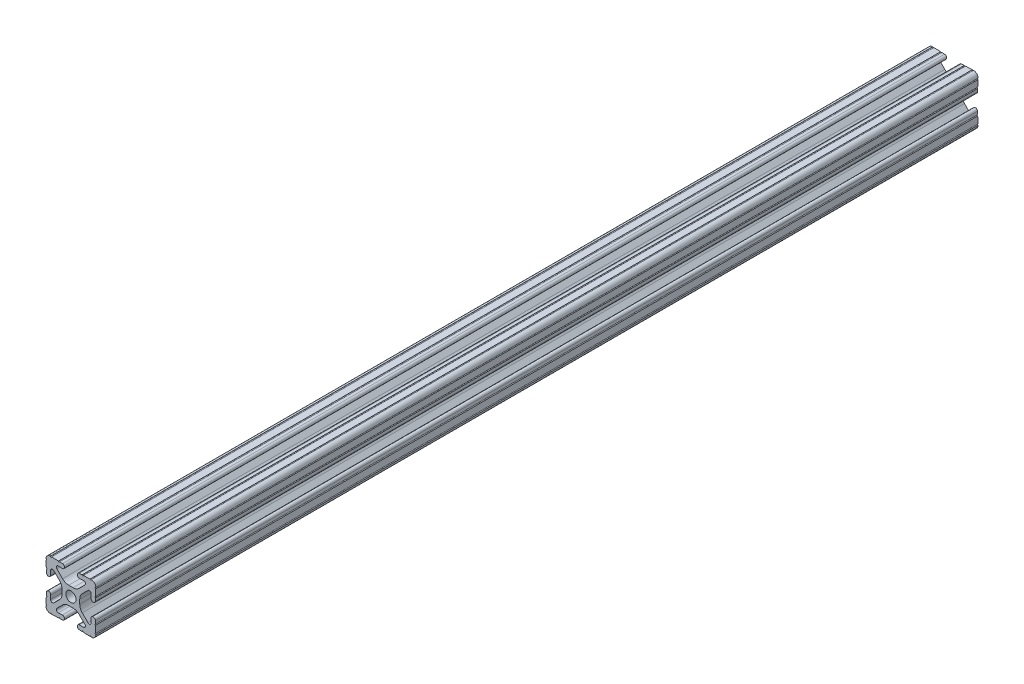
SolidWorks part; units mm, degrees
ref_plane "Front Plane" through (0, 0, 0) normal (0, 0, 1) x (1, 0, 0)
ref_plane "Top Plane" through (0, 0, 0) normal (0, 1, 0) x (1, 0, 0)
ref_plane "Right Plane" through (0, 0, 0) normal (1, 0, 0) x (0, 0, -1)
sketch "Sketch1" plane through (0, 0, 0) normal (0, 0, 1) x (1, 0, 0)
  line L0 (0, 12.7) -> (-12.7814, 12.7) construction
  line L1 (-4.5085, 0) -> (-4.5085, 2.9459)
  line L2 (-6.0437, 12.5461) -> (-10.0976, 12.6876) construction
  line L3 (-11.5616, 12.4229) -> (-4.3159, 12.1699) construction
  line L4 (-6.4364, 10.3486) -> (-6.3592, 12.5571) construction
  line L6 (-2.9459, 4.5085) -> (0, 4.5085)
  line L7 (0, 0) -> (0, 12.7) construction
  line L8 (0, 0) -> (-12.7814, 0) construction
  line L9 (0.7813, 0.7813) -> (-0.7813, -0.7813) construction
  line L10 (-2.9459, 4.5085) -> (-7.1484, 8.711)
  line L11 (-4.5085, 2.9459) -> (-8.711, 7.1484)
  line L13 (0, 0) -> (-12.7814, 12.7814) construction
  line L14 (-10.4131, 12.6987) -> (-4.3048, 12.4853)
  line L15 (-4.3048, 12.4853) -> (-4.382, 10.2769) construction
  line L16 (-4.382, 10.2769) -> (-6.4364, 10.3486)
  line L17 (-12.6987, 10.4131) -> (-12.4853, 4.3048)
  line L18 (-10.2769, 4.382) -> (-10.3486, 6.4364)
  circle A0 centre (0, 0) radius 2.6035
  arc A1 (-4.382, 10.2769) -> (-4.3048, 12.4853) centre (-4.3434, 11.3811) ccw
  arc A2 (-7.1484, 8.711) -> (-6.4364, 10.3486) centre (-6.4698, 9.3896) cw
  arc A3 (-8.711, 7.1484) -> (-10.3486, 6.4364) centre (-9.3896, 6.4698) ccw
  arc A4 (-10.2769, 4.382) -> (-12.4853, 4.3048) centre (-11.3811, 4.3434) cw
  arc A5 (-10.4131, 12.6987) -> (-12.6987, 10.4131) centre (-10.4902, 10.4902) ccw
  arc A6 (-10.4131, 12.6987) -> (-9.7821, 12.6766) centre (-10.0976, 12.6876) ccw
  arc A7 (-6.3592, 12.5571) -> (-5.7282, 12.5351) centre (-6.0437, 12.5461) ccw
  arc A8 (-12.5571, 6.3592) -> (-12.5351, 5.7282) centre (-12.5461, 6.0437) cw
  arc A9 (-12.6987, 10.4131) -> (-12.6766, 9.7821) centre (-12.6876, 10.0976) cw
  dimension "D1" = 5.207
  dimension "D5" = 14.859
  dimension "D9" = 2
  dimension "D2" = 25.4
  dimension "D12" = 0.6314
  dimension "D10" = 2.2098
  dimension "D3" = 9.017
  dimension "D4" = 9.017
  dimension "D6" = 25.4
  dimension "D7" = 6.477
  dimension "D8" = 2.2098
  dimension "D11" = 12.7
sketch "Sketch3" plane through (0, 0, 0) normal (0, 0, 1) x (1, 0, 0)
  line L0 (-2.9459, 4.5085) -> (0, 4.5085) construction
  line L1 (-2.9459, 4.5085) -> (-7.1484, 8.711) construction
  line L2 (-4.382, 10.2769) -> (-6.4364, 10.3486) construction
  line L3 (-10.4131, 12.6987) -> (-4.3048, 12.4853) construction
  line L4 (-4.5085, 0) -> (-4.5085, 2.9459) construction
  line L5 (-4.5085, 2.9459) -> (-8.711, 7.1484) construction
  line L6 (-10.2769, 4.382) -> (-10.3486, 6.4364) construction
  line L7 (-12.6987, 10.4131) -> (-12.4853, 4.3048) construction
  line L8 (-1.1153, 4.5085) -> (1.1153, 4.5085)
  line L9 (-4.2404, 5.803) -> (-7.1484, 8.711)
  line L10 (-4.382, 10.2769) -> (-6.4364, 10.3486)
  line L11 (-9.7821, 12.6766) -> (-6.3592, 12.5571)
  line L12 (-4.5085, -1.1153) -> (-4.5085, 1.1153)
  line L13 (-5.803, 4.2404) -> (-8.711, 7.1484)
  line L14 (-10.2769, 4.382) -> (-10.3486, 6.4364)
  line L15 (-12.6766, 9.7821) -> (-12.5571, 6.3592)
  line L16 (-5.7282, 12.5351) -> (-4.3048, 12.4853)
  line L17 (-12.5351, 5.7282) -> (-12.4853, 4.3048)
  line L18 (0, 0) -> (0, 12.7) construction
  line L19 (0, 0) -> (-12.7814, 0) construction
  line L20 (12.5351, 5.7282) -> (12.4853, 4.3048)
  line L21 (5.7282, 12.5351) -> (4.3048, 12.4853)
  line L22 (12.6766, 9.7821) -> (12.5571, 6.3592)
  line L23 (10.2769, 4.382) -> (10.3486, 6.4364)
  line L24 (5.803, 4.2404) -> (8.711, 7.1484)
  line L25 (4.5085, -1.1153) -> (4.5085, 1.1153)
  line L26 (9.7821, 12.6766) -> (6.3592, 12.5571)
  line L27 (4.382, 10.2769) -> (6.4364, 10.3486)
  line L28 (4.2404, 5.803) -> (7.1484, 8.711)
  line L29 (4.2404, -5.803) -> (7.1484, -8.711)
  line L30 (4.382, -10.2769) -> (6.4364, -10.3486)
  line L31 (9.7821, -12.6766) -> (6.3592, -12.5571)
  line L32 (5.803, -4.2404) -> (8.711, -7.1484)
  line L33 (10.2769, -4.382) -> (10.3486, -6.4364)
  line L34 (12.6766, -9.7821) -> (12.5571, -6.3592)
  line L35 (5.7282, -12.5351) -> (4.3048, -12.4853)
  line L36 (12.5351, -5.7282) -> (12.4853, -4.3048)
  line L37 (-12.5351, -5.7282) -> (-12.4853, -4.3048)
  line L38 (-5.7282, -12.5351) -> (-4.3048, -12.4853)
  line L39 (-12.6766, -9.7821) -> (-12.5571, -6.3592)
  line L40 (-10.2769, -4.382) -> (-10.3486, -6.4364)
  line L41 (-5.803, -4.2404) -> (-8.711, -7.1484)
  line L42 (-9.7821, -12.6766) -> (-6.3592, -12.5571)
  line L43 (-4.382, -10.2769) -> (-6.4364, -10.3486)
  line L44 (-4.2404, -5.803) -> (-7.1484, -8.711)
  line L45 (-1.1153, -4.5085) -> (1.1153, -4.5085)
  arc A0 (-10.4131, 12.6987) -> (-9.7821, 12.6766) centre (-10.0976, 12.6876) ccw construction
  arc A1 (-6.4364, 10.3486) -> (-7.1484, 8.711) centre (-6.4698, 9.3896) ccw construction
  arc A2 (-4.382, 10.2769) -> (-4.3048, 12.4853) centre (-4.3434, 11.3811) ccw construction
  arc A3 (-8.711, 7.1484) -> (-10.3486, 6.4364) centre (-9.3896, 6.4698) ccw construction
  arc A4 (-12.4853, 4.3048) -> (-10.2769, 4.382) centre (-11.3811, 4.3434) ccw construction
  arc A5 (-6.3592, 12.5571) -> (-5.7282, 12.5351) centre (-6.0437, 12.5461) ccw construction
  arc A6 (-10.4131, 12.6987) -> (-12.6987, 10.4131) centre (-10.4902, 10.4902) ccw construction
  arc A7 (-12.6766, 9.7821) -> (-12.6987, 10.4131) centre (-12.6876, 10.0976) ccw construction
  arc A8 (-12.5351, 5.7282) -> (-12.5571, 6.3592) centre (-12.5461, 6.0437) ccw construction
  arc A9 (-10.4131, 12.6987) -> (-9.7821, 12.6766) centre (-10.0976, 12.6876) ccw
  arc A10 (-6.4364, 10.3486) -> (-7.1484, 8.711) centre (-6.4698, 9.3896) ccw
  arc A11 (-4.382, 10.2769) -> (-4.3048, 12.4853) centre (-4.3434, 11.3811) ccw
  arc A12 (-8.711, 7.1484) -> (-10.3486, 6.4364) centre (-9.3896, 6.4698) ccw
  arc A13 (-12.4853, 4.3048) -> (-10.2769, 4.382) centre (-11.3811, 4.3434) ccw
  arc A14 (-6.3592, 12.5571) -> (-5.7282, 12.5351) centre (-6.0437, 12.5461) ccw
  arc A15 (-10.4131, 12.6987) -> (-12.6987, 10.4131) centre (-10.4902, 10.4902) ccw
  arc A16 (-12.6766, 9.7821) -> (-12.6987, 10.4131) centre (-12.6876, 10.0976) ccw
  arc A17 (-12.5351, 5.7282) -> (-12.5571, 6.3592) centre (-12.5461, 6.0437) ccw
  arc A18 (-1.1153, 4.5085) -> (-4.2404, 5.803) centre (-1.1153, 8.9281) cw
  arc A19 (4.5085, 1.1153) -> (5.803, 4.2404) centre (8.9281, 1.1153) cw
  arc A20 (1.1153, 4.5085) -> (4.2404, 5.803) centre (1.1153, 8.9281) ccw
  arc A21 (-4.5085, 1.1153) -> (-5.803, 4.2404) centre (-8.9281, 1.1153) ccw
  arc A22 (12.5351, 5.7282) -> (12.5571, 6.3592) centre (12.5461, 6.0437) cw
  arc A23 (12.6766, 9.7821) -> (12.6987, 10.4131) centre (12.6876, 10.0976) cw
  arc A24 (10.4131, 12.6987) -> (12.6987, 10.4131) centre (10.4902, 10.4902) cw
  arc A25 (6.3592, 12.5571) -> (5.7282, 12.5351) centre (6.0437, 12.5461) cw
  arc A26 (12.4853, 4.3048) -> (10.2769, 4.382) centre (11.3811, 4.3434) cw
  arc A27 (8.711, 7.1484) -> (10.3486, 6.4364) centre (9.3896, 6.4698) cw
  arc A28 (4.382, 10.2769) -> (4.3048, 12.4853) centre (4.3434, 11.3811) cw
  arc A29 (6.4364, 10.3486) -> (7.1484, 8.711) centre (6.4698, 9.3896) cw
  arc A30 (10.4131, 12.6987) -> (9.7821, 12.6766) centre (10.0976, 12.6876) cw
  arc A31 (10.4131, -12.6987) -> (9.7821, -12.6766) centre (10.0976, -12.6876) ccw
  arc A32 (6.4364, -10.3486) -> (7.1484, -8.711) centre (6.4698, -9.3896) ccw
  arc A33 (4.382, -10.2769) -> (4.3048, -12.4853) centre (4.3434, -11.3811) ccw
  arc A34 (8.711, -7.1484) -> (10.3486, -6.4364) centre (9.3896, -6.4698) ccw
  arc A35 (12.4853, -4.3048) -> (10.2769, -4.382) centre (11.3811, -4.3434) ccw
  arc A36 (6.3592, -12.5571) -> (5.7282, -12.5351) centre (6.0437, -12.5461) ccw
  arc A37 (10.4131, -12.6987) -> (12.6987, -10.4131) centre (10.4902, -10.4902) ccw
  arc A38 (12.6766, -9.7821) -> (12.6987, -10.4131) centre (12.6876, -10.0976) ccw
  arc A39 (12.5351, -5.7282) -> (12.5571, -6.3592) centre (12.5461, -6.0437) ccw
  arc A40 (-4.5085, -1.1153) -> (-5.803, -4.2404) centre (-8.9281, -1.1153) cw
  arc A41 (1.1153, -4.5085) -> (4.2404, -5.803) centre (1.1153, -8.9281) cw
  arc A42 (4.5085, -1.1153) -> (5.803, -4.2404) centre (8.9281, -1.1153) ccw
  arc A43 (-1.1153, -4.5085) -> (-4.2404, -5.803) centre (-1.1153, -8.9281) ccw
  arc A44 (-12.5351, -5.7282) -> (-12.5571, -6.3592) centre (-12.5461, -6.0437) cw
  arc A45 (-12.6766, -9.7821) -> (-12.6987, -10.4131) centre (-12.6876, -10.0976) cw
  arc A46 (-10.4131, -12.6987) -> (-12.6987, -10.4131) centre (-10.4902, -10.4902) cw
  arc A47 (-6.3592, -12.5571) -> (-5.7282, -12.5351) centre (-6.0437, -12.5461) cw
  arc A48 (-12.4853, -4.3048) -> (-10.2769, -4.382) centre (-11.3811, -4.3434) cw
  arc A49 (-8.711, -7.1484) -> (-10.3486, -6.4364) centre (-9.3896, -6.4698) cw
  arc A50 (-4.382, -10.2769) -> (-4.3048, -12.4853) centre (-4.3434, -11.3811) cw
  arc A51 (-6.4364, -10.3486) -> (-7.1484, -8.711) centre (-6.4698, -9.3896) cw
  arc A52 (-10.4131, -12.6987) -> (-9.7821, -12.6766) centre (-10.0976, -12.6876) cw
  circle A53 centre (0, 0) radius 2.6035 construction
  circle A54 centre (0, 0) radius 2.6035
  point P135 (4.5085, 0)
  dimension "D2" = 4.4196
extrude "Extrude1" add sketch "Sketch3" along normal mid plane 450
equation "\"D10@Sketch1\" = \"D8@Sketch1\""
equation "\"D11@Sketch1\" = \"D6@Sketch1\"/2"
equation "\"D12@Sketch1\" = \"D8@Sketch1\"/3.5"
equation "\"D2@Sketch3\" = \"D8@Sketch1\"*2"
